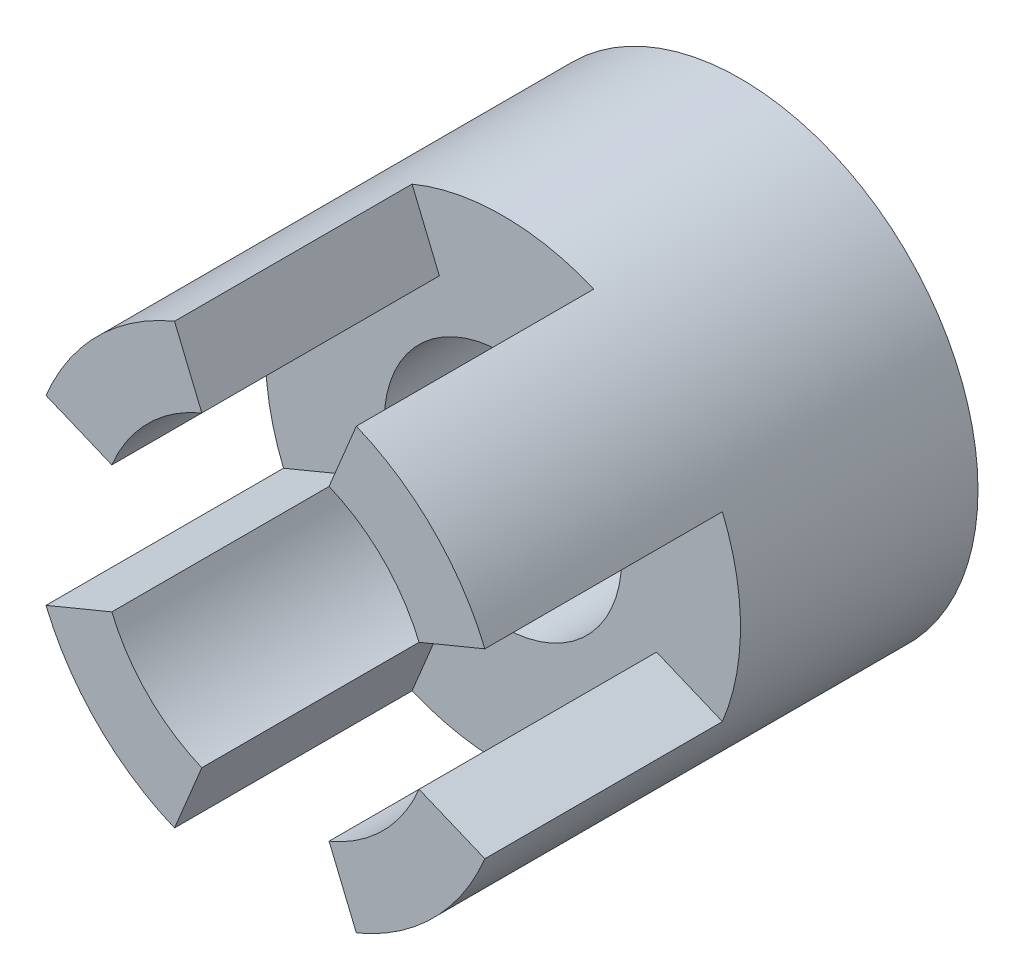
SolidWorks part; units mm, degrees
material "7050-T73510"
ref_plane "前视基准面" through (0, 0, 0) normal (0, 0, 1) x (1, 0, 0)
ref_plane "上视基准面" through (0, 0, 0) normal (0, 1, 0) x (1, 0, 0)
ref_plane "右视基准面" through (0, 0, 0) normal (1, 0, 0) x (0, 0, -1)
sketch "草图1" plane through (0, 0, 0) normal (0, 0, 1) x (1, 0, 0)
  circle A0 centre (0, 0) radius 10
  circle A1 centre (0, 0) radius 5
  dimension "D1" = 20
  dimension "D2" = 10
extrude "凸台-拉伸1" add sketch "草图1" along normal blind 10
sketch "草图2" plane through (0, 0, 10) normal (0, 0, 1) x (1, 0, 0)
  circle A1 centre (0, 0) radius 4
  circle A2 centre (0, 0) radius 10
  dimension "D1" = 8
extrude "凸台-拉伸2" add sketch "草图2" along normal blind 10
sketch "草图3" plane through (0, 0, 20) normal (0, 0, 1) x (1, 0, 0)
  line L1 (3.8268, 9.2388) -> (2.6788, 6.4672)
  line L3 (9.2388, 3.8268) -> (6.4672, 2.6788)
  line L5 (9.2388, -3.8268) -> (6.4672, -2.6788)
  line L7 (3.8268, -9.2388) -> (2.6788, -6.4672)
  line L9 (-3.8268, -9.2388) -> (-2.6788, -6.4672)
  line L11 (-9.2388, -3.8268) -> (-6.4672, -2.6788)
  line L13 (-9.2388, 3.8268) -> (-6.4672, 2.6788)
  line L15 (-3.8268, 9.2388) -> (-2.6788, 6.4672)
  line L16 (-2.6788, -6.4672) -> (-3.8268, -9.2388)
  line L17 (2.6788, 6.4672) -> (3.8268, 9.2388)
  line L20 (6.4672, 2.6788) -> (9.2388, 3.8268)
  line L21 (-6.4672, -2.6788) -> (-9.2388, -3.8268)
  line L24 (6.4672, -2.6788) -> (9.2388, -3.8268)
  line L25 (-6.4672, 2.6788) -> (-9.2388, 3.8268)
  line L28 (-2.6788, 6.4672) -> (-3.8268, 9.2388)
  line L29 (2.6788, -6.4672) -> (3.8268, -9.2388)
  arc A1 (-6.4672, 2.6788) -> (-6.4672, -2.6788) centre (0, 0) ccw
  arc A2 (-9.2388, 3.8268) -> (-9.2388, -3.8268) centre (0, 0) ccw
  arc A3 (3.8268, 9.2388) -> (-3.8268, 9.2388) centre (0, 0) ccw
  arc A4 (2.6788, 6.4672) -> (-2.6788, 6.4672) centre (0, 0) ccw
  arc A5 (9.2388, -3.8268) -> (9.2388, 3.8268) centre (0, 0) ccw
  arc A6 (6.4672, -2.6788) -> (6.4672, 2.6788) centre (0, 0) ccw
  arc A7 (-2.6788, -6.4672) -> (2.6788, -6.4672) centre (0, 0) ccw
  arc A8 (-3.8268, -9.2388) -> (3.8268, -9.2388) centre (0, 0) ccw
  point P40 (0, 0)
  circle M3 centre (0, 0) radius 10
  dimension "D1" = 14
  dimension "D2" = 20
extrude "切除-拉伸1" cut sketch "草图3" against normal blind 10 contours A4 L1 L15 M3 | A6 L5 L3 M3 | A7 L9 L7 M3 | A1 L13 L11 M3
sketch "草图4" plane through (0, 0, 20) normal (0, 0, 1) x (1, 0, 0)
  circle A0 centre (0, 0) radius 7
extrude "切除-拉伸2" cut sketch "草图4" against normal blind 10
